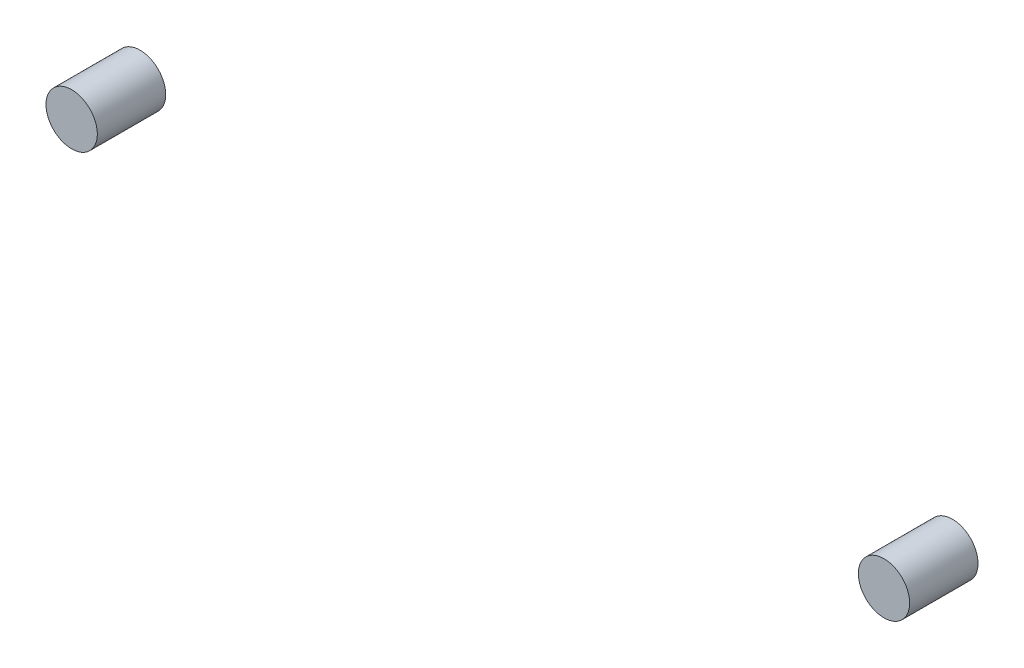
SolidWorks part; units mm, degrees
ref_plane "Front Plane" through (0, 0, 0) normal (0, 0, 1) x (1, 0, 0)
ref_plane "Top Plane" through (0, 0, 0) normal (0, 1, 0) x (1, 0, 0)
ref_plane "Right Plane" through (0, 0, 0) normal (1, 0, 0) x (0, 0, -1)
sketch "Sketch1" plane through (0, 0, 0) normal (0, 0, 1) x (1, 0, 0)
  line L0 (74.3682, 0) -> (-15.4311, 0) construction
  circle A0 centre (0, 0) radius 9.525
  circle A1 centre (301.625, 0) radius 9.525
  dimension "D2" = 19.05
  dimension "D1" = 301.625
extrude "Boss-Extrude1" add sketch "Sketch1" along normal mid plane 25.4
